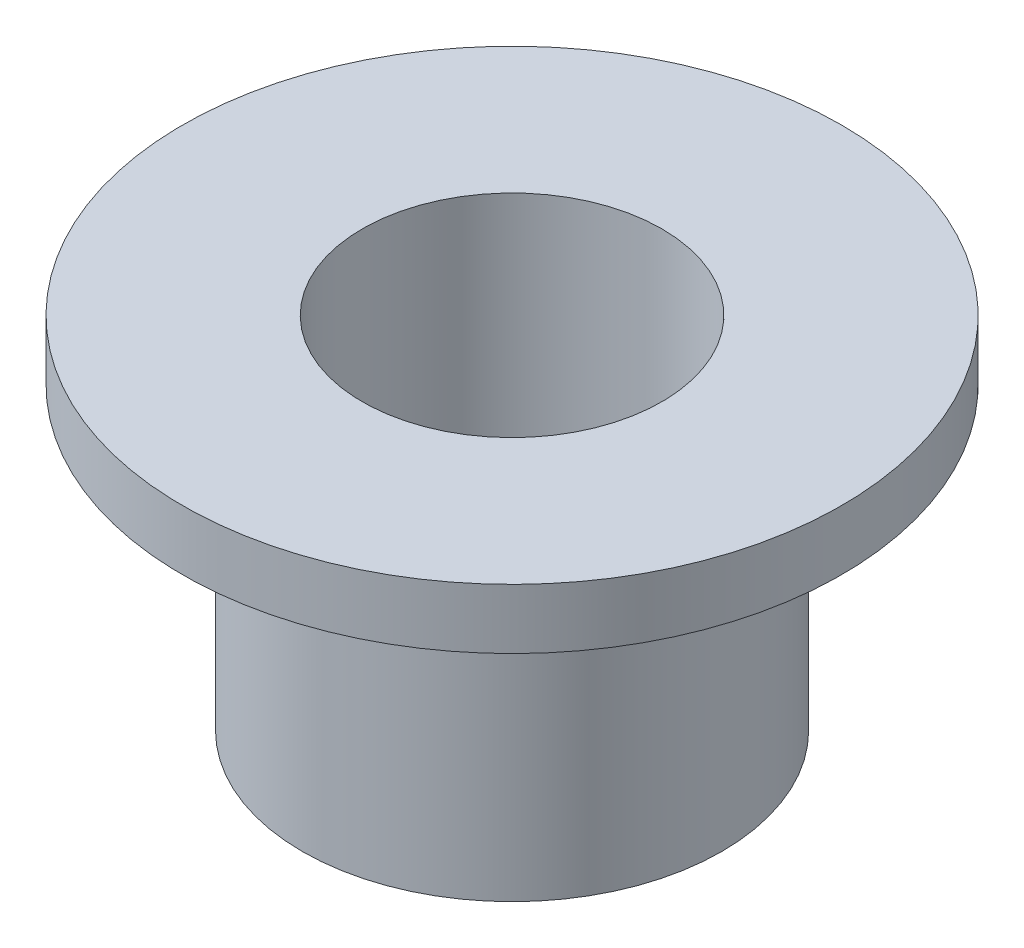
SolidWorks part; units mm, degrees
ref_plane "Front Plane" through (0, 0, 0) normal (0, 0, 1) x (1, 0, 0)
ref_plane "Top Plane" through (0, 0, 0) normal (0, 1, 0) x (1, 0, 0)
ref_plane "Right Plane" through (0, 0, 0) normal (1, 0, 0) x (0, 0, -1)
sketch "Sketch2" plane through (0, 0, 0) normal (0, 0, 1) x (1, 0, 0)
  line L0 (-2.5, 0) -> (-2.5, 6)
  line L1 (-2.5, 6) -> (-5.5, 6)
  line L2 (-5.5, 6) -> (-5.5, 5)
  line L3 (-5.5, 5) -> (-3.5, 5)
  line L4 (-3.5, 5) -> (-3.5, 0)
  line L5 (-3.5, 0) -> (-2.5, 0)
  line L6 (-2.5, 0) -> (0, 0) construction
  line L7 (0, 0) -> (0, 2.2598) construction
  point P2 (0, 2.2598)
  dimension "D1" = 1
  dimension "D2" = 2
  dimension "D3" = 1
  dimension "D4" = 6
  dimension "D5" = 2.5
  dimension "D6" = 5.5
revolve "Revolve1" add sketch "Sketch2" angle 360 about L7
